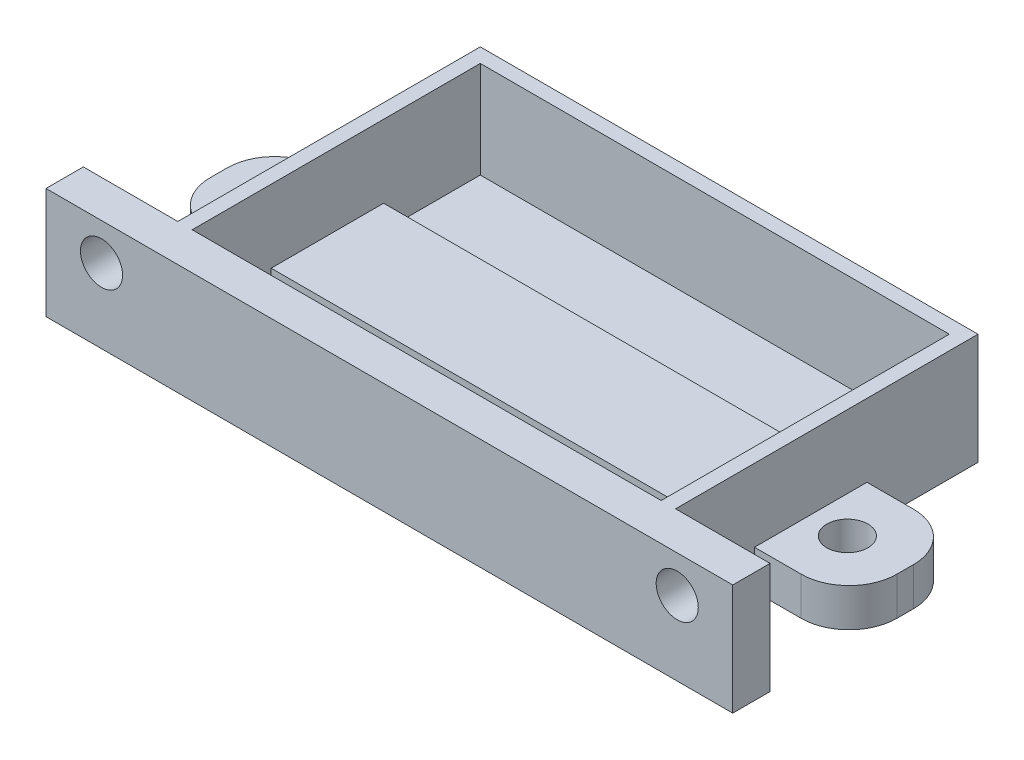
SolidWorks part; units mm, degrees
ref_plane "Front Plane" through (0, 0, 0) normal (0, 0, 1) x (1, 0, 0)
ref_plane "Top Plane" through (0, 0, 0) normal (0, 1, 0) x (1, 0, 0)
ref_plane "Right Plane" through (0, 0, 0) normal (1, 0, 0) x (0, 0, -1)
sketch "Sketch1" plane through (0, 0, 0) normal (0, 1, 0) x (1, 0, 0)
  line L1 (26, -17.75) -> (-26, -17.75)
  line L2 (26, -17.75) -> (26, 17.75)
  line L3 (26, 17.75) -> (-26, 17.75)
  line L4 (-26, -17.75) -> (-26, 17.75)
  line L5 (26, -17.75) -> (-26, 17.75) construction
  line L6 (26, 17.75) -> (-26, -17.75) construction
  point P0 (0, 0)
  dimension "D1" = 35.5
  dimension "D2" = 52
extrude "Boss-Extrude1" add sketch "Sketch1" along normal blind 11.6
shell "Shell1" thickness 1.5
sketch "Sketch2" plane through (0, 0, 17.75) normal (0, 0, 1) x (1, 0, 0)
  line L0 (-26, 0) -> (26, 11.6) construction
  line L1 (-26, 11.6) -> (26, 11.6) construction
  line L2 (35.875, 0) -> (-35.875, 0)
  line L3 (35.875, 0) -> (35.875, 11.6)
  line L4 (35.875, 11.6) -> (-35.875, 11.6)
  line L5 (-35.875, 0) -> (-35.875, 11.6)
  line L6 (35.875, 0) -> (-35.875, 11.6) construction
  line L7 (35.875, 11.6) -> (-35.875, 0) construction
  point P4 (0, 5.8)
  point P5 (0, 5.8)
  dimension "D1" = 71.75
extrude "Boss-Extrude2" add sketch "Sketch2" against normal blind 3.9
sketch "Sketch3" plane through (0, 0, 0) normal (0, -1, 0) x (1, 0, 0)
  line L0 (-35.875, 13.85) -> (-26, 13.85) construction
  line L1 (35.875, -6.15) -> (-35.875, -6.15)
  line L2 (35.875, -6.15) -> (35.875, 5.6)
  line L3 (35.875, 5.6) -> (-35.875, 5.6)
  line L4 (-35.875, -6.15) -> (-35.875, 5.6)
  line L5 (35.875, -6.15) -> (-35.875, 5.6) construction
  line L6 (35.875, 5.6) -> (-35.875, -6.15) construction
  point P0 (0, -0.275)
  point P5 (0, 0)
  dimension "D1" = 71.75
  dimension "D2" = 11.75
  dimension "D3" = 20
extrude "Boss-Extrude3" add sketch "Sketch3" against normal blind 4
fillet "Fillet1" radius 5 4 edges at (35.875, 2, 5.6) (35.875, 2, -6.15) (-35.875, 2, 5.6) (-35.875, 2, -6.15)
sketch "Sketch4" plane through (0, 4, 0) normal (0, 1, 0) x (1, 0, 0)
  line L0 (0, -1000) -> (0, 49000) construction
  line L2 (31.975, -991.9674) -> (31.975, 49008.0326) construction
  line L3 (35.875, 1.15) -> (35.875, -0.6) construction
  line L4 (-1041.3825, 0.275) -> (48958.6175, 0.275) construction
  circle A0 centre (-29.825, 0.275) radius 2.15
  circle A1 centre (29.825, 0.275) radius 2.15
  point P11 (0, 0)
  dimension "D1" = 4.3
  dimension "D2" = 3.9
extrude "Cut-Extrude1" cut sketch "Sketch4" against normal through all
sketch "Sketch5" plane through (0, 0, 17.75) normal (0, 0, 1) x (1, 0, 0)
  line L0 (0, -1000) -> (0, 49000) construction
  line L1 (-35.875, 0) -> (35.875, 0) construction
  line L2 (32.275, -1006.6333) -> (32.275, 48993.3667) construction
  line L3 (-971.3566, 9.95) -> (49028.6434, 9.95) construction
  line L4 (35.875, 0) -> (35.875, 11.6) construction
  line L5 (-35.875, 11.6) -> (35.875, 11.6) construction
  circle A0 centre (-30.075, 7.75) radius 2.2
  circle A1 centre (30.075, 7.75) radius 2.2
  point P9 (0, 0)
  dimension "D1" = 4.4
  dimension "D2" = 3.6
  dimension "D3" = 1.65
extrude "Cut-Extrude2" cut sketch "Sketch5" against normal through all
